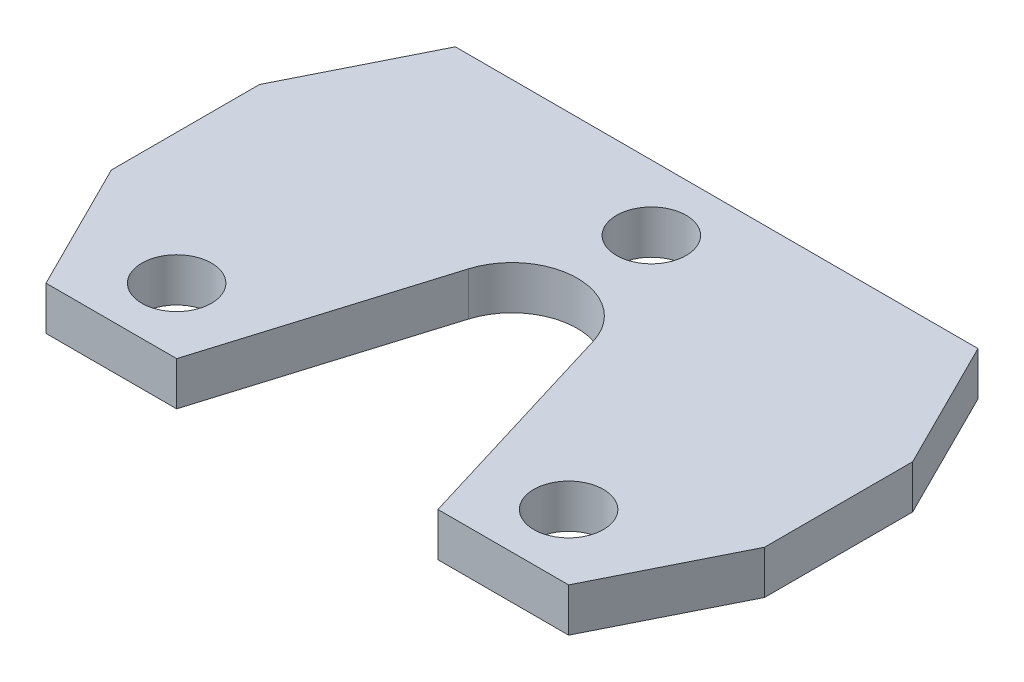
SolidWorks part; units mm, degrees
ref_plane "Front" through (0, 0, 0) normal (0, 0, 1) x (1, 0, 0)
ref_plane "Top" through (0, 0, 0) normal (0, 1, 0) x (1, 0, 0)
ref_plane "Right" through (0, 0, 0) normal (1, 0, 0) x (0, 0, -1)
sketch "Sketch1" plane through (0, 0, 0) normal (0, 1, 0) x (1, 0, 0)
  line L0 (-60, 27.301) -> (60, 27.301)
  line L1 (-60, 27.301) -> (-75, -2.699)
  line L2 (-75, -2.699) -> (-75, -36.699)
  line L3 (-75, -36.699) -> (-60, -66.699)
  line L4 (-60, -66.699) -> (-30, -66.699)
  line L6 (-30, -66.699) -> (-14.349, -15.3275)
  line L7 (60, 27.301) -> (75, -2.699)
  line L8 (75, -2.699) -> (75, -36.699)
  line L9 (75, -36.699) -> (60, -66.699)
  line L10 (60, -66.699) -> (30, -66.699)
  line L12 (30, -66.699) -> (14.3486, -15.3274)
  arc A0 (14.3486, -15.3274) -> (-14.349, -15.3275) centre (-0.0002, -19.699) ccw
  circle A1 centre (-45, -51.699) radius 8
  circle A2 centre (0, 12.301) radius 8
  circle A3 centre (45, -51.699) radius 8
  dimension "D19" = 16
  dimension "D20" = 16
  dimension "D21" = 16
  dimension "D22" = 15
  dimension "D1" = 120
  dimension "D2" = 34
  dimension "D3" = 15
  dimension "D4" = 15
  dimension "D5" = 15
  dimension "D6" = 30
  dimension "D7" = 15
  dimension "D8" = 30
  dimension "D9" = 34
  dimension "D10" = 30
  dimension "D11" = 30
  dimension "D12" = 30
  dimension "D13" = 30
  dimension "D14" = 15
  dimension "D15" = 15
  dimension "D16" = 15
  dimension "D17" = 15
  dimension "D18" = 15
  dimension "D23" = 150
  dimension "D24" = 94
  dimension "D25" = 47
extrude "Boss-Extrude1" add sketch "Sketch1" along normal blind 10
